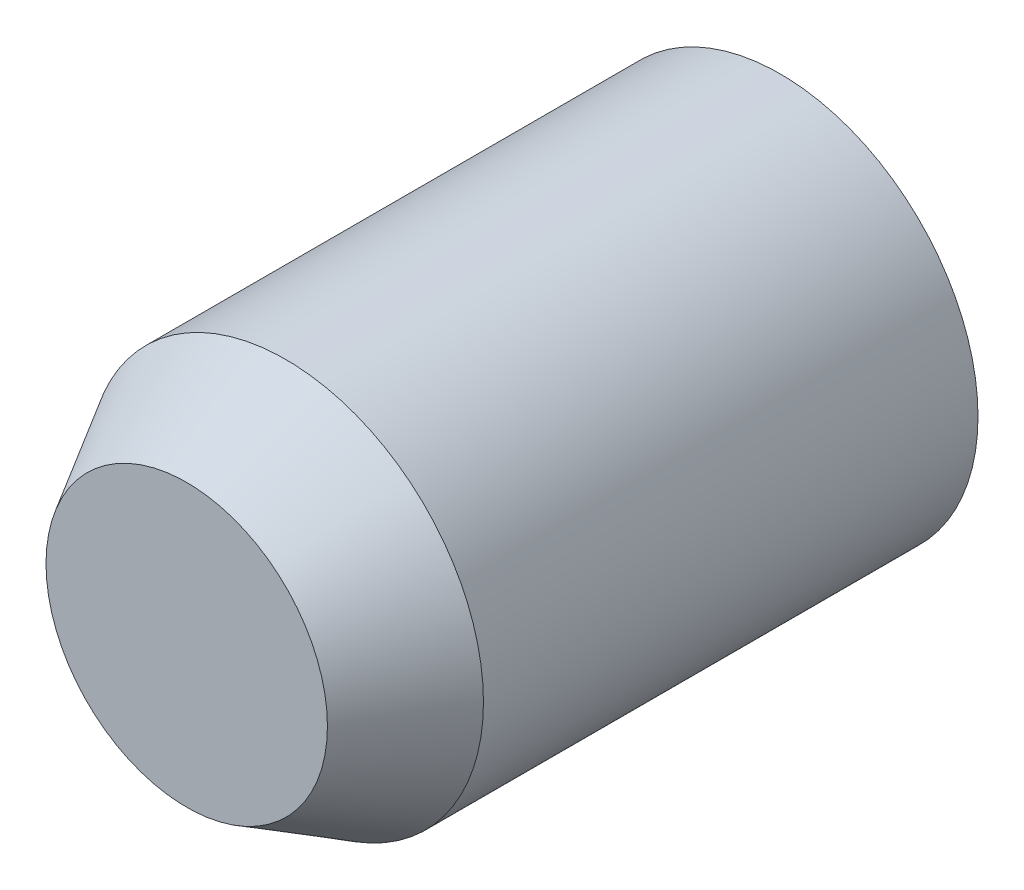
SolidWorks part; units mm, degrees
ref_plane "Front Plane" through (0, 0, 0) normal (0, 0, 1) x (1, 0, 0)
ref_plane "Top Plane" through (0, 0, 0) normal (0, 1, 0) x (1, 0, 0)
ref_plane "Right Plane" through (0, 0, 0) normal (1, 0, 0) x (0, 0, -1)
sketch "Sketch1" plane through (0, 0, 0) normal (0, 0, 1) x (1, 0, 0)
  circle A0 centre (0, 0) radius 1
  dimension "D1" = 2
extrude "Boss-Extrude1" add sketch "Sketch1" along normal blind 3
chamfer "Chamfer1" distance 0.5 angle 30 1 edges at (1, 0, 3)
sketch "Sketch2" plane through (0, 0, 0) normal (0, 0, -1) x (-1, 0, 0)
  line L0 (0, 0) -> (0.8083, 0) construction
  line L1 (0.8083, 0) -> (0.4041, 0.7)
  line L2 (0.4041, 0.7) -> (-0.4041, 0.7)
  line L3 (-0.4041, 0.7) -> (-0.8083, 0)
  line L4 (-0.8083, 0) -> (-0.4041, -0.7)
  line L5 (-0.4041, -0.7) -> (0.4041, -0.7)
  line L6 (0.4041, -0.7) -> (0.8083, 0)
  circle A0 centre (0, 0) radius 0.7 construction
  dimension "D1" = 1.4
extrude "Cut-Extrude1" cut sketch "Sketch2" against normal blind 1
